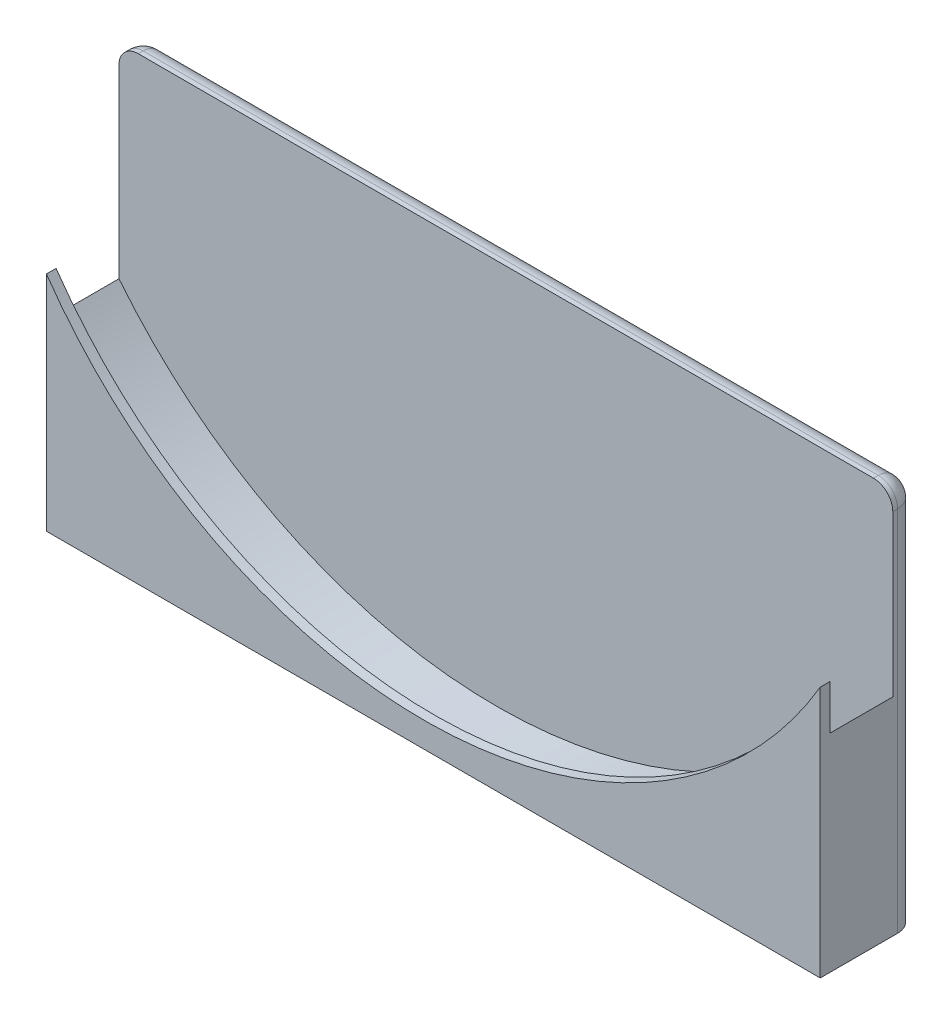
SolidWorks part; units mm, degrees
ref_plane "Front Plane" through (0, 0, 0) normal (0, 0, 1) x (1, 0, 0)
ref_plane "Top Plane" through (0, 0, 0) normal (0, 1, 0) x (1, 0, 0)
ref_plane "Right Plane" through (0, 0, 0) normal (1, 0, 0) x (0, 0, -1)
sketch "Sketch1" plane through (0, 0, 0) normal (0, 1, 0) x (1, 0, 0)
  line L1 (37.3343, -12.0644) -> (-42.6657, -12.0644)
  line L2 (37.3343, -12.0644) -> (37.3343, -2.0644)
  line L3 (37.3343, -2.0644) -> (-42.6657, -2.0644)
  line L4 (-42.6657, -12.0644) -> (-42.6657, -2.0644)
  dimension "D1" = 80
  dimension "D2" = 10
extrude "Boss-Extrude1" add sketch "Sketch1" along normal blind 40
sketch "Sketch2" plane through (0, 0, 12.0644) normal (0, 0, 1) x (1, 0, 0)
  circle A0 centre (-3.6251, 50.0938) radius 47.5
  dimension "D1" = 95
extrude "Cut-Extrude1" cut sketch "Sketch2" against normal blind 7.5
ref_plane "Plane1" through (0, 0, 11.0644) normal (0, 0, 1) x (1, 0, 0)
sketch "Sketch3" plane through (0, 0, 11.0644) normal (0, 0, 1) x (1, 0, 0)
  circle A0 centre (-3.6251, 50.0938) radius 50
  arc A1 (-42.6657, 23.0368) -> (37.3343, 26.0402) centre (-3.6251, 50.0938) ccw construction
  dimension "D1" = 100
extrude "Cut-Extrude2" cut sketch "Sketch3" against normal up to surface (6.5 mm away) up to face at (-2.46, 26.7914, 4.5644)
fillet "Fillet1" radius 2 2 edges at (37.3343, 40, 3.3144) (-42.6657, 40, 3.3144)
fillet "Fillet2" radius 2 5 edges at (-42.6657, 19, 2.0644) (-42.0799, 39.4142, 2.0644) (-2.6657, 40, 2.0644) (36.7486, 39.4142, 2.0644) (37.3343, 19, 2.0644)
